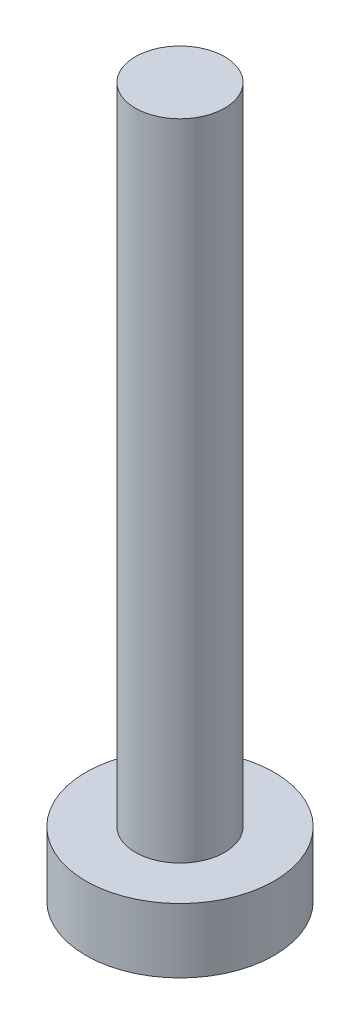
SolidWorks part; units mm, degrees
ref_plane "Front Plane" through (0, 0, 0) normal (0, 0, 1) x (1, 0, 0)
ref_plane "Top Plane" through (0, 0, 0) normal (0, 1, 0) x (1, 0, 0)
ref_plane "Right Plane" through (0, 0, 0) normal (1, 0, 0) x (0, 0, -1)
sketch "Sketch2" plane through (0, 0, 0) normal (0, 1, 0) x (1, 0, 0)
  circle A0 centre (0, 0) radius 1.9
  dimension "D1" = 3.8
extrude "Boss-Extrude1" add sketch "Sketch2" along normal blind 1.3
sketch "Sketch3" plane through (0, 1.3, 0) normal (0, 1, 0) x (1, 0, 0)
  circle A0 centre (0, 0) radius 0.9
  dimension "D1" = 1.8
extrude "Boss-Extrude2" add sketch "Sketch3" along normal blind 13
sketch "Sketch4" plane through (0, 0, 0) normal (0, -1, 0) x (1, 0, 0)
  line L1 (0.7506, 0) -> (0.3753, 0.65)
  line L2 (0.3753, 0.65) -> (-0.3753, 0.65)
  line L3 (-0.3753, 0.65) -> (-0.7506, 0)
  line L4 (-0.7506, 0) -> (-0.3753, -0.65)
  line L5 (-0.3753, -0.65) -> (0.3753, -0.65)
  line L6 (0.3753, -0.65) -> (0.7506, 0)
  circle A0 centre (0, 0) radius 0.65 construction
  dimension "D1" = 1.3
extrude "Cut-Extrude1" cut sketch "Sketch4" against normal blind 0.7
equation "\"Length\"=13"
equation "\"D1@Boss-Extrude2\"=\"Length\""
